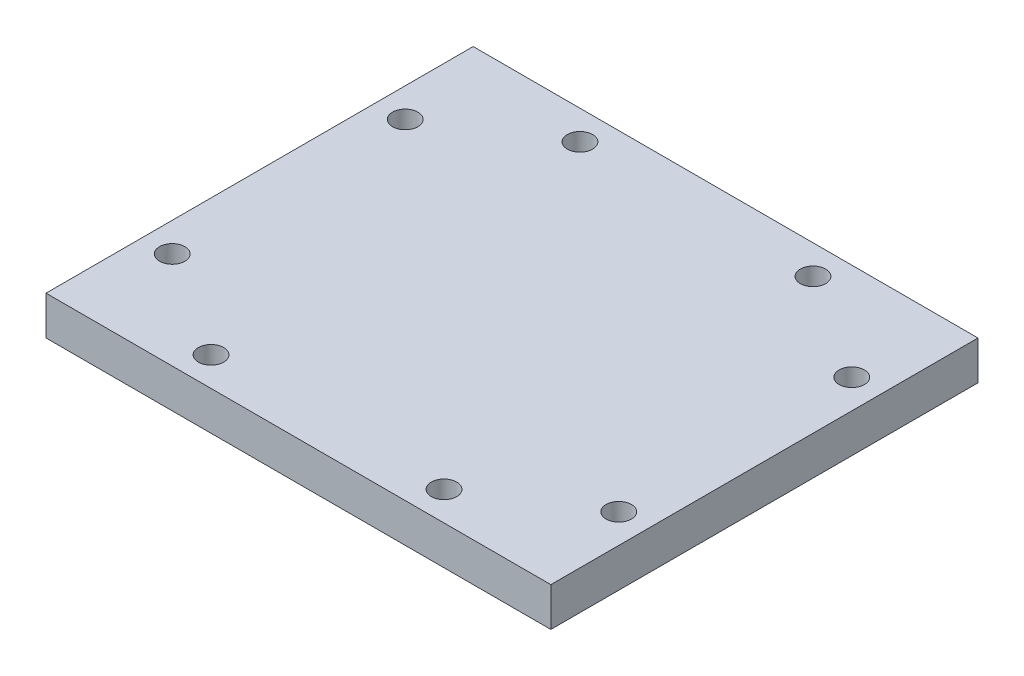
SolidWorks part; units mm, degrees
material "6061 Alloy"
ref_plane "Front Plane" through (0, 0, 0) normal (0, 0, 1) x (1, 0, 0)
ref_plane "Top Plane" through (0, 0, 0) normal (0, 1, 0) x (1, 0, 0)
ref_plane "Right Plane" through (0, 0, 0) normal (1, 0, 0) x (0, 0, -1)
sketch "Sketch2" plane through (0, 0, 0) normal (0, 1, 0) x (1, 0, 0)
  line L1 (32.5, -27.5) -> (-32.5, -27.5)
  line L2 (32.5, -27.5) -> (32.5, 27.5)
  line L3 (32.5, 27.5) -> (-32.5, 27.5)
  line L4 (-32.5, -27.5) -> (-32.5, 27.5)
  line L5 (32.5, -27.5) -> (-32.5, 27.5) construction
  line L6 (32.5, 27.5) -> (-32.5, -27.5) construction
  point P0 (0, 0)
  dimension "D1" = 55
  dimension "D2" = 65
extrude "Boss-Extrude1" add sketch "Sketch2" along normal blind 5
sketch "Sketch3" plane through (0, 0, 0) normal (0, -1, 0) x (1, 0, 0)
  line L1 (28.75, -23.75) -> (-28.75, -23.75)
  line L2 (28.75, -23.75) -> (28.75, 23.75)
  line L3 (28.75, 23.75) -> (-28.75, 23.75)
  line L4 (-28.75, -23.75) -> (-28.75, 23.75)
  line L5 (28.75, -23.75) -> (-28.75, 23.75) construction
  line L6 (28.75, 23.75) -> (-28.75, -23.75) construction
  line L7 (15, -23.75) -> (-15, -23.75)
  line L8 (15, -23.75) -> (15, 23.75)
  line L9 (15, 23.75) -> (-15, 23.75)
  line L10 (-15, -23.75) -> (-15, 23.75)
  line L11 (15, -23.75) -> (-15, 23.75) construction
  line L12 (15, 23.75) -> (-15, -23.75) construction
  line L13 (28.75, -15) -> (-28.75, -15)
  line L14 (28.75, -15) -> (28.75, 15)
  line L15 (28.75, 15) -> (-28.75, 15)
  line L16 (-28.75, -15) -> (-28.75, 15)
  line L17 (28.75, -15) -> (-28.75, 15) construction
  line L18 (28.75, 15) -> (-28.75, -15) construction
  point P0 (0, 0)
  point P5 (0, 0)
  point P11 (0, 0)
  dimension "D1" = 57.5
  dimension "D2" = 47.5
  dimension "D3" = 30
  dimension "D4" = 30
hole_wizard "#4 Clearance Hole1" positions "Sketch4" profile "Sketch5" hole size "#4" standard "ANSI Inch" end condition up to next
sketch "Sketch4" plane through (0, 0, 0) normal (0, -1, 0) x (-1, 0, 0)
  point P0 (-28.75, 15)
  point P3 (-15, 23.75)
  point P6 (15, 23.75)
  point P9 (28.75, 15)
  point P12 (28.75, -15)
  point P15 (15, -23.75)
  point P18 (-15, -23.75)
  point P21 (-28.75, -15)
sketch "Sketch5" plane through (28.75, 0, -15) normal (1, 0, 0) x (0, 0, -1)
  line L0 (0, 0) -> (0, 5)
  line L1 (0, 5) -> (1.6319, 5)
  line L2 (1.6319, 5) -> (1.6319, 0)
  line L5 (1.6319, 0) -> (0, 0)
  line L11 (0, -6.35) -> (0, 107.95) construction
  dimension "Thru Hole Dia." = 3.2639
  dimension "Thru Hole Depth" = 5
sketch "Sketch6" plane through (0, 0, 0) normal (0, -1, 0) x (1, 0, 0)
  line L1 (-32.5, 27.5) -> (-29.9, 27.5)
  line L2 (-32.5, 27.5) -> (-32.5, -27.5)
  line L3 (-32.5, -27.5) -> (-29.9, -27.5)
  line L4 (-29.9, 27.5) -> (-29.9, -27.5)
  line L5 (32.5, 27.5) -> (39.9, 27.5)
  line L6 (32.5, 27.5) -> (32.5, -27.5)
  line L7 (32.5, -27.5) -> (39.9, -27.5)
  line L8 (39.9, 27.5) -> (39.9, -27.5)
  dimension "D1" = 69.8
  dimension "D2" = 7.4
